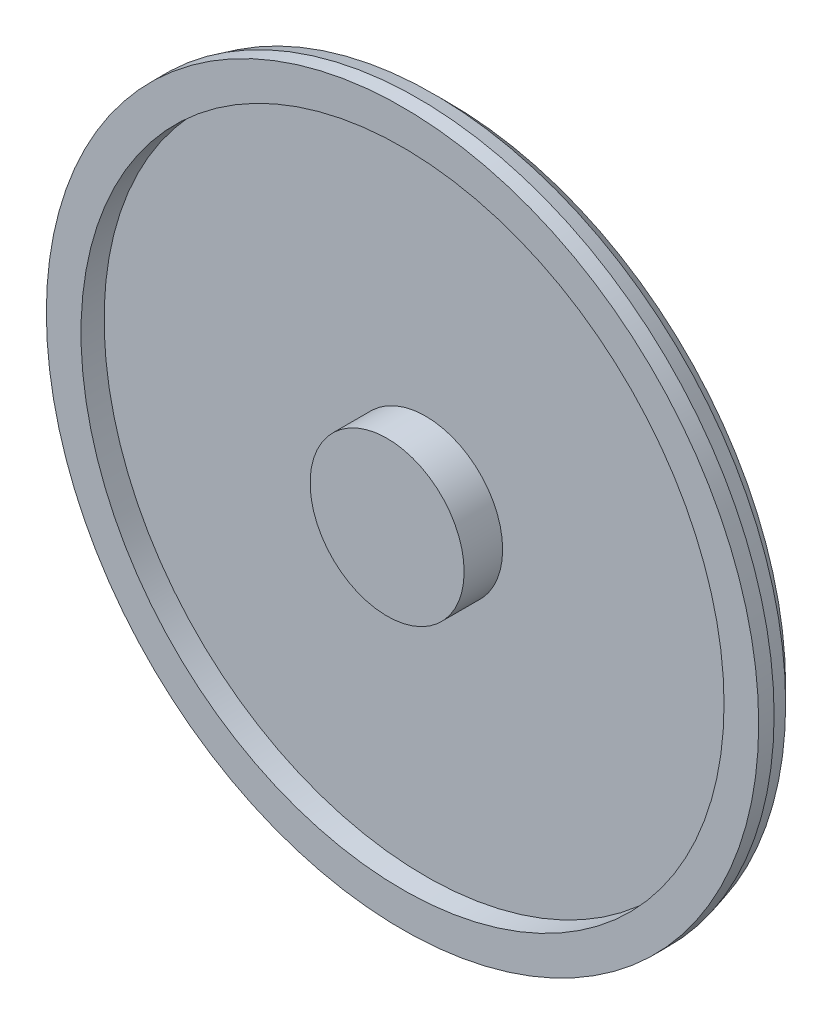
SolidWorks part; units mm, degrees
material "1060 Alloy"
ref_plane "Front Plane" through (0, 0, 0) normal (0, 0, 1) x (1, 0, 0)
ref_plane "Top Plane" through (0, 0, 0) normal (0, 1, 0) x (1, 0, 0)
ref_plane "Right Plane" through (0, 0, 0) normal (1, 0, 0) x (0, 0, -1)
sketch "Sketch1" plane through (0, 0, 0) normal (1, 0, 0) x (0, 0, -1)
  line L0 (-404.9793, 0) -> (404.9793, 0) construction
  line L1 (0, 0) -> (0, 100)
  line L2 (0, 100) -> (50, 100)
  line L3 (50, 100) -> (50, 417.5)
  line L4 (50, 417.5) -> (20, 417.5)
  line L5 (20, 417.5) -> (20, 462.5)
  line L6 (20, 462.5) -> (40, 462.5)
  line L7 (40, 462.5) -> (60.4904, 457.0096)
  line L8 (60.4904, 457.0096) -> (80, 437.5)
  line L9 (80, 437.5) -> (80, 0)
  line L10 (80, 0) -> (0, 0)
  point P9 (20, 440)
  point P14 (0, 0)
  dimension "D1" = 200
  dimension "D2" = 30
  dimension "D3" = 60
  dimension "D4" = 925
  dimension "D5" = 875
  dimension "D6" = 80
  dimension "D7" = 45
  dimension "D8" = 20
  dimension "D9" = 15
  dimension "D10" = 45
revolve "Revolve1" add sketch "Sketch1" angle 360 about L0
equation "\"A\"= 60"
equation "\"B\"= 925"
equation "\"D3@Sketch1\"=\"A\""
equation "\"D4@Sketch1\"=\"B\""
equation "\"D5@Sketch1\"=\"B\"-50"
equation "\"D6@Sketch1\"=\"A\"+20"
